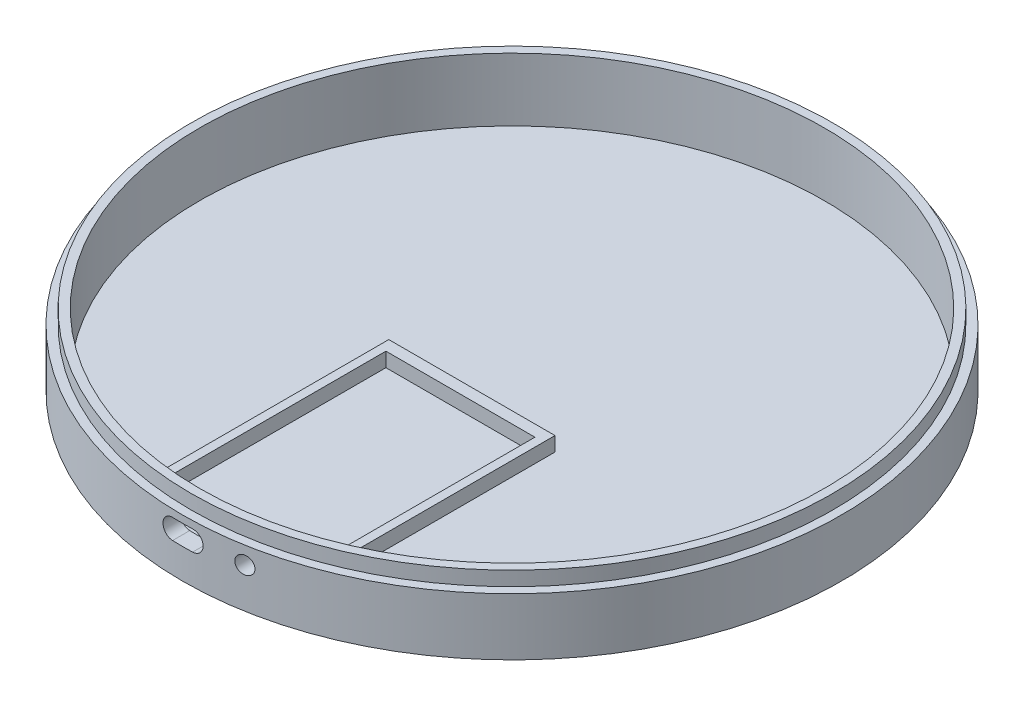
SolidWorks part; units mm, degrees
ref_plane "Front Plane" through (0, 0, 0) normal (0, 0, 1) x (1, 0, 0)
ref_plane "Top Plane" through (0, 0, 0) normal (0, 1, 0) x (1, 0, 0)
ref_plane "Right Plane" through (0, 0, 0) normal (1, 0, 0) x (0, 0, -1)
sketch "Sketch2" plane through (0, 0, 0) normal (0, 1, 0) x (1, 0, 0)
  circle A0 centre (0, 0) radius 115
  dimension "D1" = 230
extrude "Boss-Extrude1" add sketch "Sketch2" along normal blind 20
sketch "Sketch3" plane through (0, 20, 0) normal (0, 1, 0) x (1, 0, 0)
  circle A0 centre (0, 0) radius 112
  circle A1 centre (0, 0) radius 115 construction
  dimension "D1" = 3
extrude "Boss-Extrude5" add sketch "Sketch3" along normal blind 5 contours A0
sketch "Sketch6" plane through (0, 25, 0) normal (0, 1, 0) x (1, 0, 0)
  circle A0 centre (0, 0) radius 109
  circle A1 centre (0, 0) radius 112 construction
  dimension "D1" = 3
extrude "Cut-Extrude2" cut sketch "Sketch6" against normal blind 22 contours A0
sketch "Sketch9" plane through (0, 3, 0) normal (0, 1, 0) x (1, 0, 0)
  line L0 (0, -105.8982) -> (0, 0) construction
  line L1 (-29, -104) -> (29, -104)
  line L2 (-29, -104) -> (-29, -14)
  line L3 (29, -104) -> (29, -14)
  line L4 (-29, -14) -> (29, -14)
  circle A0 centre (0, 0) radius 109 construction
  point P3 (0, -104)
  dimension "D1" = 58
  dimension "D2" = 29
  dimension "D3" = 90
  dimension "D4" = 104
extrude "Boss-Extrude9" add sketch "Sketch9" along normal blind 5
sketch "Sketch10" plane through (0, 8, 0) normal (0, 1, 0) x (1, 0, 0)
  line L0 (-26, -104) -> (26, -104)
  line L1 (-26, -104) -> (-26, -18)
  line L2 (26, -104) -> (26, -18)
  line L3 (-26, -18) -> (26, -18)
  line L4 (-29, -104) -> (29, -104) construction
  line L5 (-29, -104) -> (29, -104) construction
  line L6 (29, -104) -> (29, -14) construction
  dimension "D1" = 86
  dimension "D2" = 52
  dimension "D3" = 3
extrude "Cut-Extrude3" cut sketch "Sketch10" against normal blind 5
sketch "Sketch12" plane through (0, 0, 0) normal (0, 0, 1) x (1, 0, 0)
  line L0 (0, 20) -> (0, -23.6328) construction
  line L1 (115, 20) -> (-115, 20) construction
  line L2 (-3.5, 14) -> (3.5, 14) construction
  line L3 (-3.5, 17.5) -> (3.5, 17.5)
  line L4 (-3.5, 10.5) -> (3.5, 10.5)
  line L5 (-115, 0) -> (115, 0) construction
  arc A0 (-3.5, 17.5) -> (-3.5, 10.5) centre (-3.5, 14) ccw
  arc A1 (3.5, 10.5) -> (3.5, 17.5) centre (3.5, 14) ccw
  point P7 (0, 14)
  point P14 (0, 14)
  point P15 (0, 14)
  dimension "D2" = 0
  dimension "D1" = 14
  dimension "D3" = 7
extrude "Cut-Extrude4" cut sketch "Sketch12" along normal through all
sketch "Sketch13" plane through (0, 0, 0) normal (0, 0, 1) x (1, 0, 0)
  line L0 (3.5, 10.5) -> (-3.5, 10.5) construction
  line L1 (0, -1.29) -> (0, 40.0657) construction
  circle A0 centre (20, 14) radius 3
  point P4 (0, 0)
  dimension "D1" = 6
  dimension "D2" = 3.5
  dimension "D3" = 20
extrude "Cut-Extrude5" cut sketch "Sketch13" along normal through all contours A0
